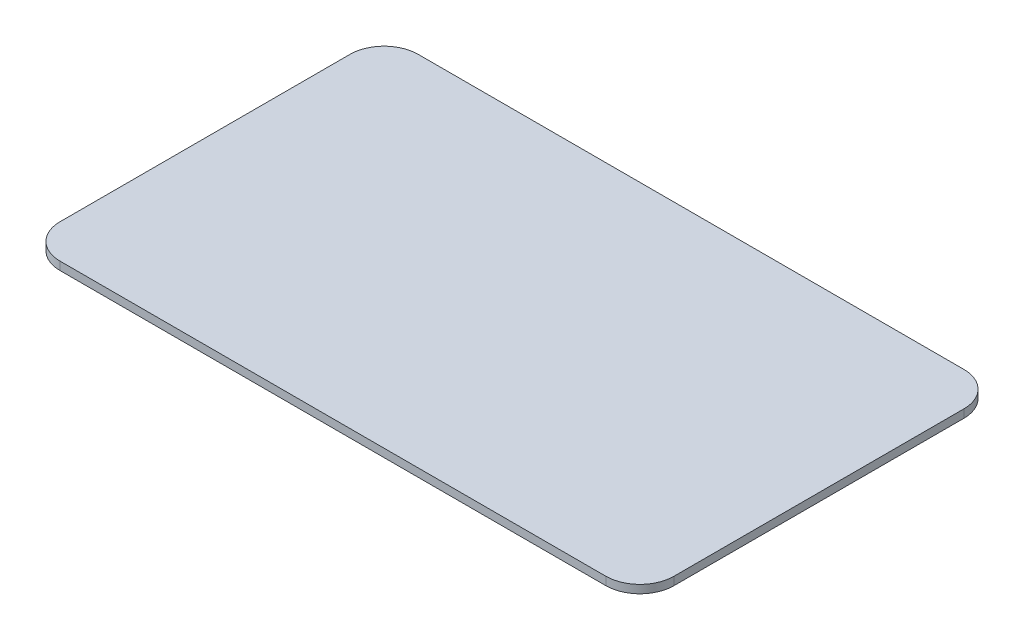
SolidWorks part; units mm, degrees
ref_plane "Front Plane" through (0, 0, 0) normal (0, 0, 1) x (1, 0, 0)
ref_plane "Top Plane" through (0, 0, 0) normal (0, 1, 0) x (1, 0, 0)
ref_plane "Right Plane" through (0, 0, 0) normal (1, 0, 0) x (0, 0, -1)
sketch "Sketch1" plane through (0, 0, 0) normal (0, 1, 0) x (1, 0, 0)
  line L1 (57.15, 33.3375) -> (-57.15, 33.3375)
  line L2 (57.15, 33.3375) -> (57.15, -33.3375)
  line L3 (57.15, -33.3375) -> (-57.15, -33.3375)
  line L4 (-57.15, 33.3375) -> (-57.15, -33.3375)
  line L5 (57.15, 33.3375) -> (-57.15, -33.3375) construction
  line L6 (57.15, -33.3375) -> (-57.15, 33.3375) construction
  point P0 (0, 0)
  dimension "D1" = 66.675
  dimension "D2" = 114.3
extrude "Boss-Extrude1" add sketch "Sketch1" along normal blind 1.524
fillet "Fillet1" radius 6.35 4 edges at (-57.15, 0.762, 33.3375) (57.15, 0.762, 33.3375) (57.15, 0.762, -33.3375) (-57.15, 0.762, -33.3375)
